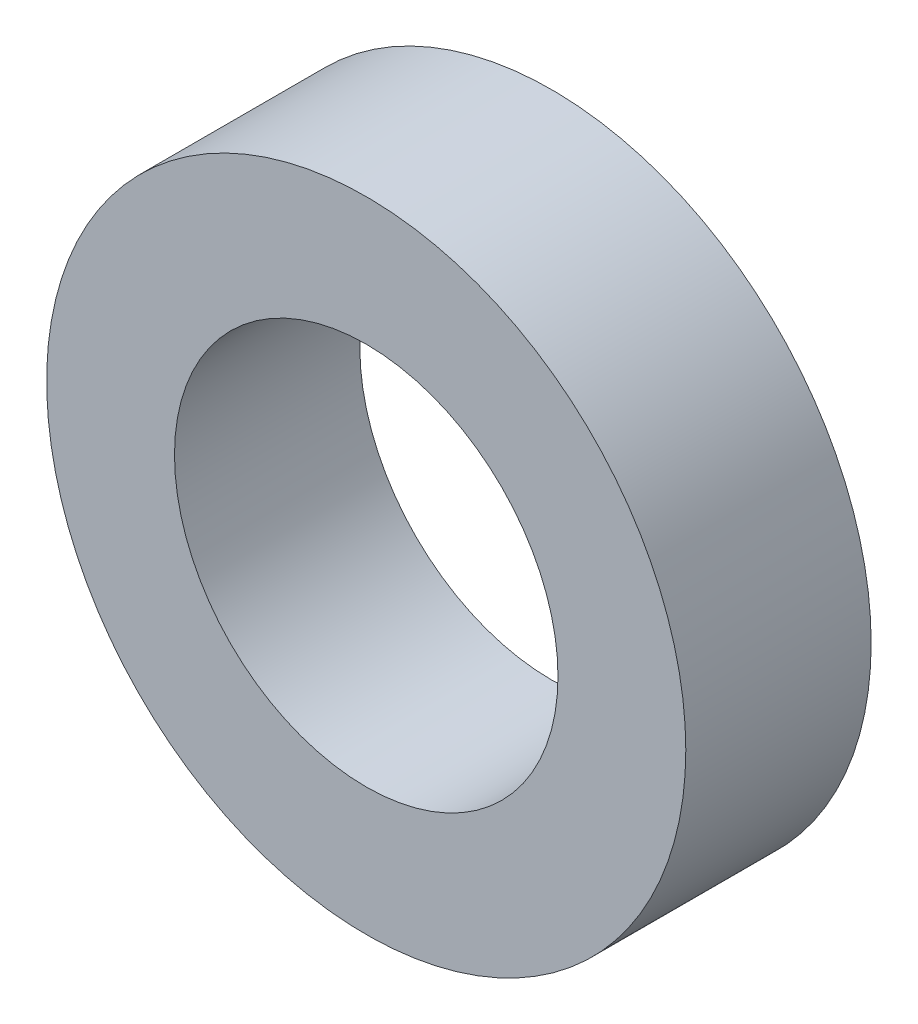
SolidWorks part; units mm, degrees
material "Acrylic (Medium-high impact)"
ref_plane "Front Plane" through (0, 0, 0) normal (0, 0, 1) x (1, 0, 0)
ref_plane "Top Plane" through (0, 0, 0) normal (0, 1, 0) x (1, 0, 0)
ref_plane "Right Plane" through (0, 0, 0) normal (1, 0, 0) x (0, 0, -1)
sketch "Sketch1" plane through (0, 0, 0) normal (0, 0, 1) x (1, 0, 0)
  circle A0 centre (0, 0) radius 3
  circle A1 centre (0, 0) radius 5
  dimension "D1" = 6
  dimension "D2" = 10
extrude "Boss-Extrude1" add sketch "Sketch1" along normal blind 2.9
equation "\"smallPulleyTeeth\"= 15"
equation "\"largePulleyTeeth\"= 30"
equation "\"eighthThick\"= 2.9mm"
equation "\"sixteenthThick\" = 1.7mm"
equation "\"quarterThick\"=6.0mm"
equation "\"OD\" = 145mm"
equation "\"puckAngle\" = 60.5deg"
equation "\"puckDiam\" = 76.5mm"
equation "\"axlePress\" = 5.9mm"
equation "\"press\" = 0.2mm"
equation "\"wheelClear\" = 0.3mm"
equation "\"10-32clear\" = 4.8mm"
equation "\"6-32clear\" = 3.3mm"
equation "\"8-32clear\" = 4.0mm"
equation "\"D1@Boss-Extrude1\"=\"eighthThick\""
